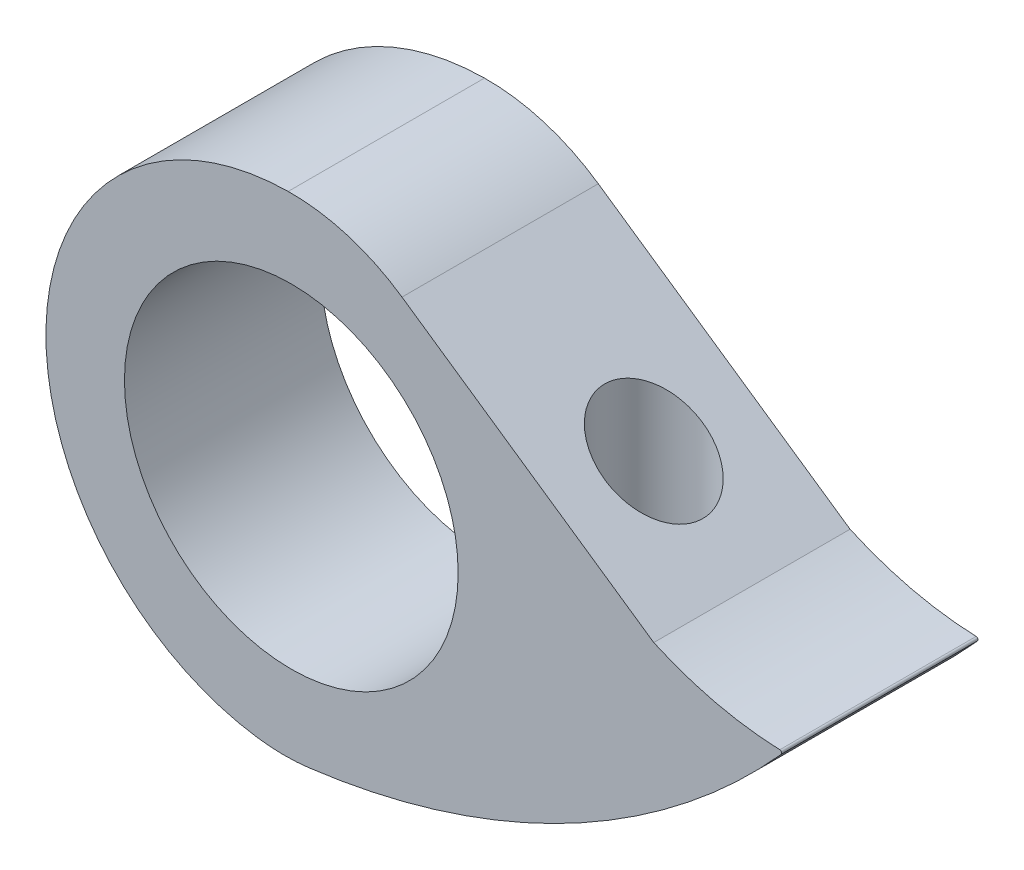
SolidWorks part; units mm, degrees
ref_plane "Front Plane" through (0, 0, 0) normal (0, 0, 1) x (1, 0, 0)
ref_plane "Top Plane" through (0, 0, 0) normal (0, 1, 0) x (1, 0, 0)
ref_plane "Right Plane" through (0, 0, 0) normal (1, 0, 0) x (0, 0, -1)
sketch "Sketch1" plane through (0, 0, 0) normal (0, 0, 1) x (1, 0, 0)
  line L0 (1.032, 3.0026) -> (4.6899, 0.4844)
  circle A0 centre (0, 0) radius 2.159
  circle A1 centre (0, 0) radius 3.175 construction
  arc A3 (4.6899, 0.4844) -> (6.3747, 0.0973) centre (6.4874, 4.4477) ccw
  arc A4 (0, -3.175) -> (6.3747, 0.0973) centre (-0.9961, 6.6109) ccw
  arc A5 (1.032, 3.0026) -> (0, -3.175) centre (0, 0) ccw
  dimension "D1" = 4.318
  dimension "D2" = 6.35
  dimension "D3" = 4.3518
  dimension "D4" = 9.8365
  dimension "D5" = 1.032
  dimension "D6" = 4.6899
  dimension "D7" = 6.3747
  dimension "D8" = 6.4874
  dimension "D9" = 0.9961
extrude "Boss-Extrude1" add sketch "Sketch1" along normal blind 2.54
fillet "Fillet2" radius 2.54 2 edges at (0, -3.175, 1.27) (1.032, 3.0026, 1.27)
fillet "Fillet3" radius 0.0254 1 edges at (6.3747, 0.0973, 1.27)
sketch "Sketch6" plane through (0, 0, 0) normal (0, 1, 0) x (1, 0, 0)
  line L0 (4.6899, -2.54) -> (4.6899, 0) construction
  line L1 (4.6899, 0) -> (1.4322, 0) construction
  circle A0 centre (3.4199, -1.27) radius 0.635
  dimension "D1" = 1.27
  dimension "D2" = 1.27
  dimension "D3" = 1.27
extrude "Cut-Extrude1" cut sketch "Sketch6" against normal through all both and the other way through all
